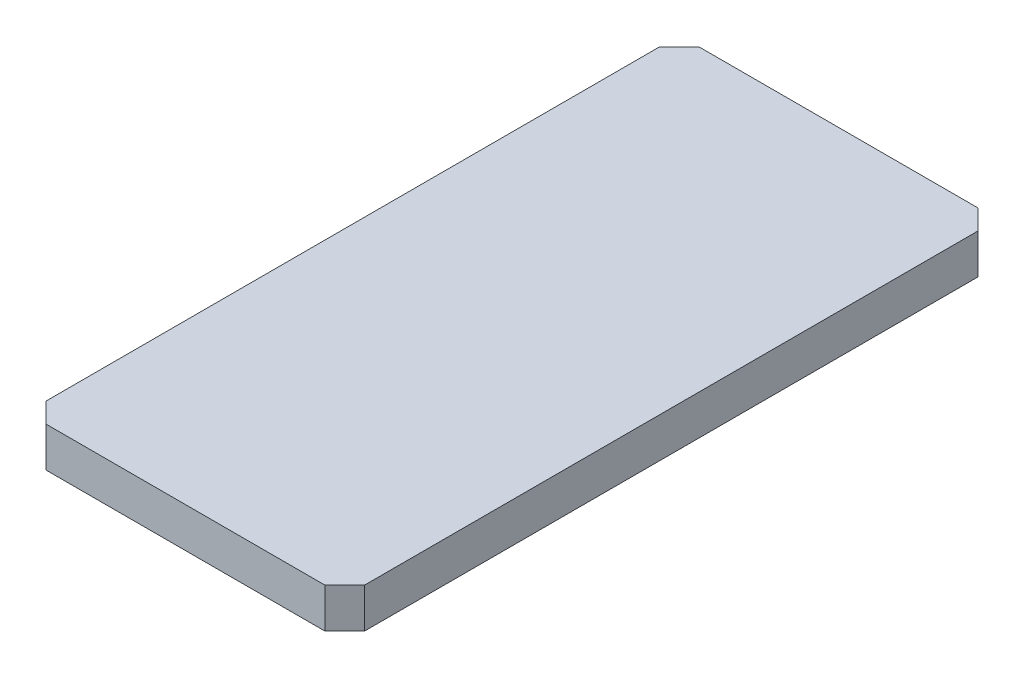
SolidWorks part; units mm, degrees
ref_plane "Front Plane" through (0, 0, 0) normal (0, 0, 1) x (1, 0, 0)
ref_plane "Top Plane" through (0, 0, 0) normal (0, 1, 0) x (1, 0, 0)
ref_plane "Right Plane" through (0, 0, 0) normal (1, 0, 0) x (0, 0, -1)
sketch "Sketch1" plane through (0, 0, 0) normal (0, 1, 0) x (1, 0, 0)
  line L1 (0, 0) -> (40, 0)
  line L2 (0, 0) -> (0, 81.9921)
  line L3 (0, 81.9921) -> (40, 81.9921)
  line L4 (40, 0) -> (40, 81.9921)
  line L7 (5, 77.437) -> (35, 77.437)
  line L8 (35, 77.437) -> (35, 57.437)
  line L9 (35, 57.437) -> (5, 57.437)
  line L10 (5, 57.437) -> (5, 77.437)
  dimension "D4" = 30
extrude "Boss-Extrude4" add sketch "Sketch1" along normal blind 5 contours L4 L3 L2 L1
chamfer "Chamfer3" distance 2.5 angle 45 1 edges at (40, 2.5, -81.9921)
chamfer "Chamfer4" distance 2.5 angle 45 1 edges at (0, 2.5, -81.9921)
chamfer "Chamfer5" distance 2.5 angle 45 1 edges at (0, 2.5, 0)
chamfer "Chamfer6" distance 2.5 angle 45 1 edges at (40, 2.5, 0)
sketch "Sketch5" plane through (0, 0, 0) normal (0, 1, 0) x (1, 0, 0)
  line L0 (7.5, 62.9921) -> (32.5, 62.9921)
  line L1 (2.5, 81.9921) -> (37.5, 81.9921) construction
  line L2 (40, 2.5) -> (40, 79.4921) construction
  line L3 (0, 2.5) -> (0, 79.4921) construction
  line L4 (36.5218, 69.9921) -> (36.4694, 69.9921)
  line L5 (7.5, 76.9921) -> (32.5, 76.9921)
  line L6 (32.5, 62.9921) -> (32.5, 65.4921)
  line L7 (7.5, 74.4921) -> (32.5, 74.4921) construction
  line L8 (32.5, 76.9921) -> (32.5, 74.4921)
  line L9 (7.5, 76.9921) -> (7.5, 74.4921)
  line L10 (32.5, 74.4921) -> (32.5, 65.4921) construction
  line L11 (32.5, 65.4921) -> (7.5, 65.4921) construction
  line L12 (7.5, 65.4921) -> (7.5, 74.4921) construction
  arc A0 (7.5, 76.9921) -> (7.5, 62.9921) centre (7.5, 69.9921) ccw
  arc A1 (32.5, 76.9921) -> (32.5, 62.9921) centre (32.5, 69.9921) cw
  circle A3 centre (36.4694, 69.9921) radius 1.5
  dimension "D8" = 7
  dimension "D9" = 7.5
  dimension "D10" = 7.5
  dimension "D3" = 2.5
  dimension "D5" = 3
  dimension "D1" = 7
  dimension "D2" = 25
  dimension "D4" = 25
  dimension "D6" = 5
  dimension "D7" = 14
  dimension "D12" = 2.5
ref_plane "Plane2" through (0, -10, 0) normal (0, -1, 0) x (-1, 0, 0)
sketch "Sketch7" plane through (0, -10, 0) normal (0, -1, 0) x (-1, 0, 0)
extrude "Cut-Extrude5" cut sketch "Sketch5" along normal blind 0.5
